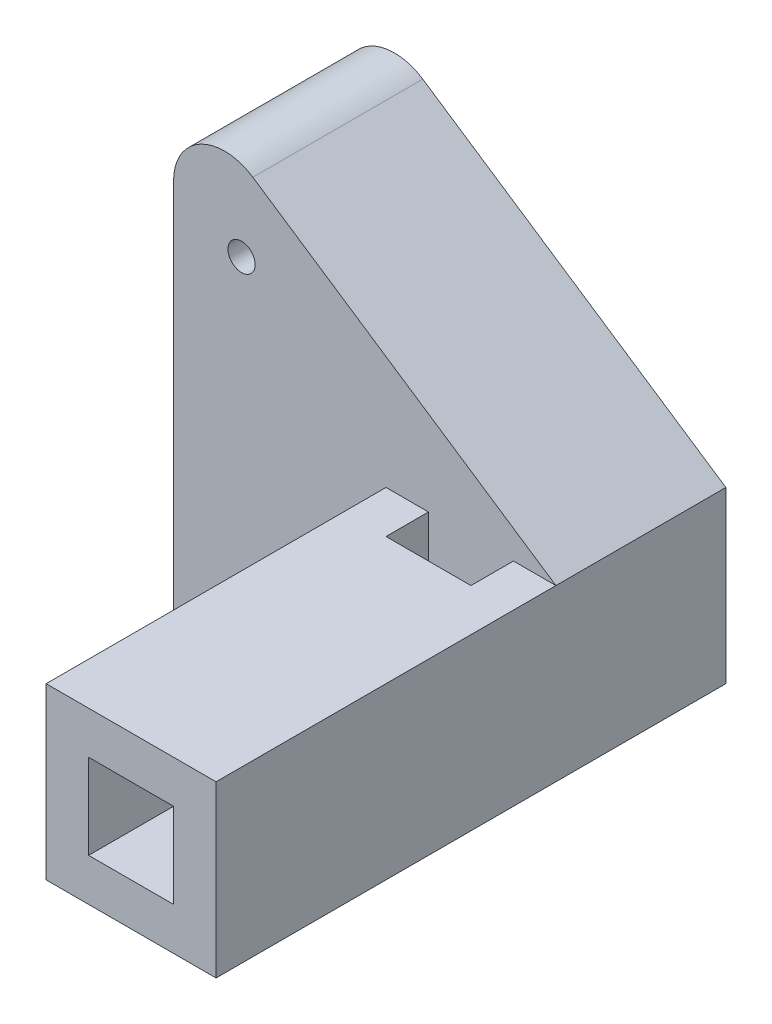
SolidWorks part; units mm, degrees
ref_plane "前视基准面" through (0, 0, 0) normal (0, 0, 1) x (1, 0, 0)
ref_plane "上视基准面" through (0, 0, 0) normal (0, 1, 0) x (1, 0, 0)
ref_plane "右视基准面" through (0, 0, 0) normal (1, 0, 0) x (0, 0, -1)
sketch "草图1" plane through (0, 0, 0) normal (0, 0, 1) x (1, 0, 0)
  line L1 (0, 0) -> (10, 0)
  line L2 (0, 0) -> (0, 10)
  line L3 (0, 10) -> (10, 10)
  line L4 (10, 0) -> (10, 10)
  line L5 (-5, -5) -> (15, -5)
  line L6 (-5, -5) -> (-5, 15)
  line L7 (-5, 15) -> (15, 15)
  line L8 (15, -5) -> (15, 15)
  dimension "D1" = 10
  dimension "D2" = 10
  dimension "D3" = 5
  dimension "D4" = 5
  dimension "D5" = 5
  dimension "D6" = 5
extrude "凸台-拉伸1" add sketch "草图1" along normal blind 60
sketch "草图2" plane through (0, 15, 0) normal (0, 1, 0) x (1, 0, 0)
  line L0 (-5, -60) -> (-5, 0) construction
  line L1 (0, -20) -> (10, -20)
  line L2 (0, -20) -> (0, -25)
  line L3 (0, -25) -> (10, -25)
  line L4 (10, -20) -> (10, -25)
  line L5 (15, -60) -> (15, 0) construction
  line L6 (15, 0) -> (-5, 0) construction
  dimension "D1" = 5
  dimension "D2" = 5
  dimension "D3" = 20
  dimension "D4" = 5
extrude "切除-拉伸1" cut sketch "草图2" against normal blind 80
sketch "草图4" plane through (0, 0, 0) normal (0, 0, -1) x (-1, 0, 0)
  line L1 (30, 33.7889) -> (30, -23.7889)
  line L3 (5, -5) -> (5, 15)
  line L4 (-15, 15) -> (20.6718, 38.7812)
  line L5 (-15, -5) -> (20.6718, -28.7812)
  line L6 (-15, -5) -> (5, -5)
  line L7 (-15, 15) -> (5, 15)
  circle A0 centre (22, -20) radius 1.6
  circle A1 centre (22, 30) radius 1.6
  arc A2 (20.6718, 38.7812) -> (30, 33.7889) centre (24, 33.7889) cw
  arc A3 (30, -23.7889) -> (20.6718, -28.7812) centre (24, -23.7889) cw
  point P16 (30, 45)
  point P19 (30, -35)
  dimension "D7" = 6
  dimension "D8" = 3.2
  dimension "D1" = 25
  dimension "D2" = 30
  dimension "D3" = 30
  dimension "D4" = 8
  dimension "D5" = 15
  dimension "D6" = 15
extrude "凸台-拉伸3" add sketch "草图4" against normal up to surface (20 mm away) up to face at (5, 12.5, 20)
chamfer "倒角1" distance 1 angle 45 4 edges at (5, 10, 0) (10, 5, 0) (5, 0, 0) (0, 5, 0)
